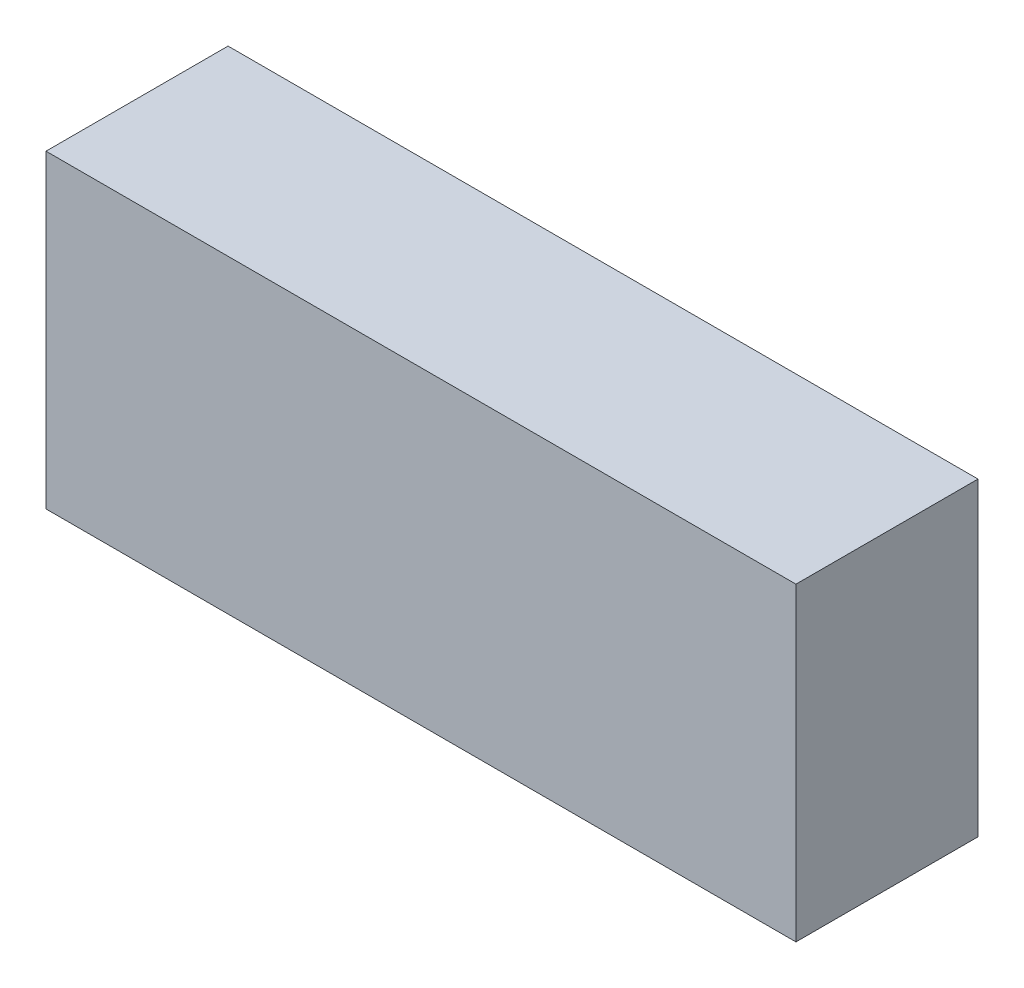
SolidWorks part; units mm, degrees
ref_plane "Front Plane" through (0, 0, 0) normal (0, 0, 1) x (1, 0, 0)
ref_plane "Top Plane" through (0, 0, 0) normal (0, 1, 0) x (1, 0, 0)
ref_plane "Right Plane" through (0, 0, 0) normal (1, 0, 0) x (0, 0, -1)
sketch "Sketch1" plane through (0, 0, 0) normal (0, 0, 1) x (1, 0, 0)
  line L1 (-61.7894, 25.5293) -> (61.7894, 25.5293)
  line L2 (-61.7894, 25.5293) -> (-61.7894, -25.5293)
  line L3 (-61.7894, -25.5293) -> (61.7894, -25.5293)
  line L4 (61.7894, 25.5293) -> (61.7894, -25.5293)
  line L5 (-61.7894, 25.5293) -> (61.7894, -25.5293) construction
  line L6 (-61.7894, -25.5293) -> (61.7894, 25.5293) construction
  point P0 (0, 0)
extrude "Boss-Extrude1" add sketch "Sketch1" along normal blind 30
